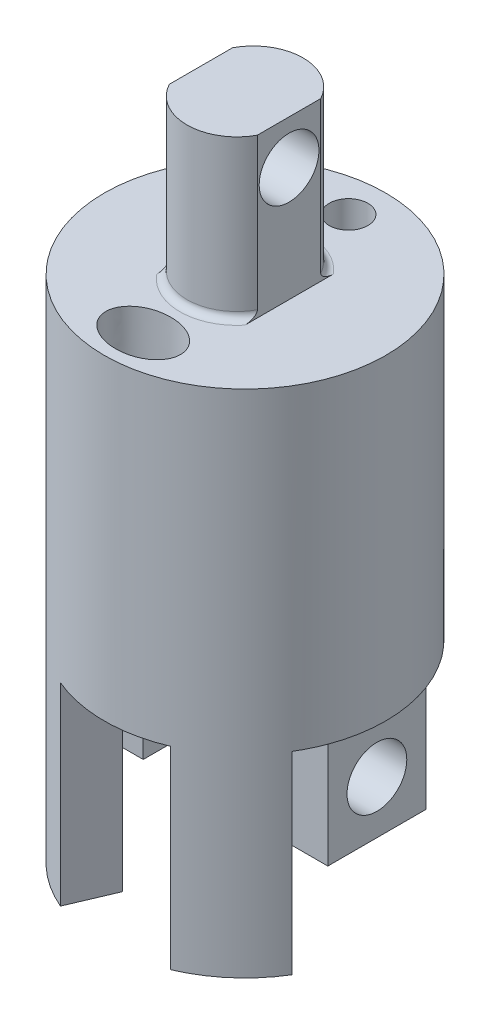
SolidWorks part; units mm, degrees
ref_plane "Front Plane" through (0, 0, 0) normal (0, 0, 1) x (1, 0, 0)
ref_plane "Top Plane" through (0, 0, 0) normal (0, 1, 0) x (1, 0, 0)
ref_plane "Right Plane" through (0, 0, 0) normal (1, 0, 0) x (0, 0, -1)
sketch "Sketch2" plane through (0, 0, 0) normal (0, 1, 0) x (1, 0, 0)
  circle A0 centre (0, 0) radius 8
  dimension "D1" = 16
extrude "Boss-Extrude1" add sketch "Sketch2" along normal blind 18
sketch "Sketch4" plane through (0, 18, 0) normal (0, 1, 0) x (1, 0, 0)
  line L1 (-55, 0) -> (55, 0) construction
  line L2 (2.5045, -1.8) -> (2.5045, 1.8)
  line L5 (0, -55) -> (0, 55) construction
  line L6 (-2.5045, -1.8) -> (-2.5045, 1.8)
  arc A2 (-2.5045, 1.8) -> (2.5045, 1.8) centre (0, 0.4642) cw
  arc A3 (-2.5045, -1.8) -> (2.5045, -1.8) centre (0, -0.4642) ccw
  point P5 (2.5045, 0)
  point P8 (1.2, 0)
  dimension "D1" = 1.8
  dimension "D2" = 5.009
extrude "Boss-Extrude3" add sketch "Sketch4" along normal blind 9
fillet "Fillet1" radius 0.4 2 edges at (0, 18, -3.3027) (0, 18, 3.3027)
sketch "Sketch12" plane through (0, 0, 0) normal (0, 1, 0) x (1, 0, 0)
  circle A1 centre (0, 5.8879) radius 1.1
  dimension "D2" = 2.2
extrude "Cut-Extrude2" cut sketch "Sketch12" along normal through all
sketch "Sketch13" plane through (-2.5045, 0, 0) normal (-1, 0, 0) x (0, 0, 1)
  line L0 (-1.8, 27) -> (1.8, 27) construction
  circle A0 centre (0, 24.5) radius 1.7
  dimension "D1" = 3.4
  dimension "D2" = 2.5
extrude "Cut-Extrude3" cut sketch "Sketch13" against normal through all
sketch "Sketch14" plane through (0, 0, 0) normal (0, -1, 0) x (1, 0, 0)
  line L0 (8.8, 0) -> (-8.8, 0) construction
  line L1 (-2.9977, -2.79) -> (-7.4977, -2.79)
  line L2 (-2.9977, -2.79) -> (-2.9977, 2.79)
  line L3 (-2.9977, 2.79) -> (-7.4977, 2.79)
  line L4 (-7.4977, -2.79) -> (-7.4977, 2.79)
  line L5 (-2.9977, -2.79) -> (-7.4977, 2.79) construction
  line L6 (-2.9977, 2.79) -> (-7.4977, -2.79) construction
  line L7 (0, -8.8) -> (0, 8.8) construction
  line L8 (2.9977, -2.79) -> (2.9977, 2.79)
  line L9 (2.9977, -2.79) -> (7.4977, -2.79)
  line L10 (7.4977, -2.79) -> (7.4977, 2.79)
  line L11 (2.9977, 2.79) -> (7.4977, 2.79)
  circle A0 centre (0, 0) radius 8 construction
  point P0 (-5.2477, 0)
  dimension "D1" = 5.58
  dimension "D2" = 4.5
extrude "Boss-Extrude5" add sketch "Sketch14" along normal blind 6
sketch "Sketch15" plane through (7.4977, 0, 0) normal (1, 0, 0) x (0, 0, -1)
  circle A0 centre (0, -3) radius 1.7
  dimension "D1" = 3.4
extrude "Cut-Extrude4" cut sketch "Sketch15" against normal through all
sketch "Sketch18" plane through (0, 18, 0) normal (0, 1, 0) x (1, 0, 0)
  ellipse E0 centre (0, -5.7886) end of major axis (-2.125, -5.7886) minor radius 1.5636
  dimension "D1" = 4.25
extrude "Cut-Extrude5" cut sketch "Sketch18" against normal through all
sketch "Sketch19" plane through (0, 0, 0) normal (0, -1, 0) x (1, 0, 0)
  line L0 (-6.8326, 4.1613) -> (-4.999, 3.0446)
  line L1 (-3.1315, 7.3616) -> (-2.0803, 4.8905)
  line L2 (0, -8.8) -> (0, 8.8) construction
  line L3 (3.1315, 7.3616) -> (2.0803, 4.8905)
  line L4 (6.8326, 4.1613) -> (4.999, 3.0446)
  arc A0 (-6.8326, 4.1613) -> (-3.1315, 7.3616) centre (0, 0) cw
  arc A1 (7.4977, 2.79) -> (-7.4977, 2.79) centre (0, 0) ccw construction
  arc A2 (-4.999, 3.0446) -> (-2.0803, 4.8905) centre (181.0616, -287.9181) cw
  arc A3 (6.8326, 4.1613) -> (3.1315, 7.3616) centre (0, 0) ccw
  arc A4 (4.999, 3.0446) -> (2.0803, 4.8905) centre (-181.0616, -287.9181) ccw
extrude "Boss-Extrude6" add sketch "Sketch19" along normal blind 11
sketch "Sketch20" plane through (0, 0, 0) normal (0, -1, 0) x (1, 0, 0)
  line L2 (2.9119, -2.79) -> (2.9119, 2.79)
  line L4 (-2.9977, -2.79) -> (-2.9977, 2.79)
  line L8 (-2.9977, 2.79) -> (-2.9977, 4.3727)
  line L9 (-2.9977, 4.3727) -> (2.9119, 4.3727)
  line L10 (2.9119, 2.79) -> (2.9119, 4.3727)
  line L12 (-2.9977, -2.79) -> (-2.9977, -4.3063)
  line L13 (-2.9977, -4.3063) -> (2.9119, -4.3063)
  line L14 (2.9119, -2.79) -> (2.9119, -4.3063)
  point P0 (0, 0)
extrude "Cut-Extrude6" cut sketch "Sketch20" against normal blind 3.5
